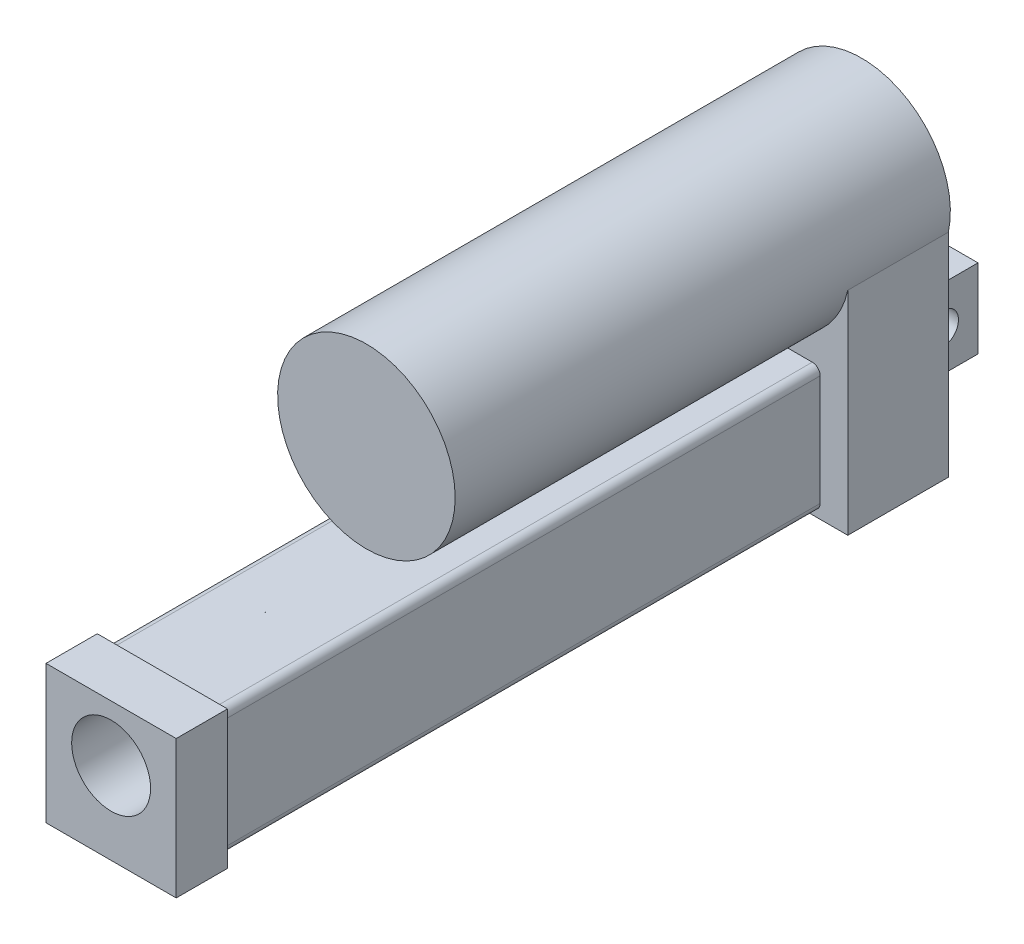
SolidWorks part; units mm, degrees
ref_plane "Front Plane" through (0, 0, 0) normal (0, 0, 1) x (1, 0, 0)
ref_plane "Top Plane" through (0, 0, 0) normal (0, 1, 0) x (1, 0, 0)
ref_plane "Right Plane" through (0, 0, 0) normal (1, 0, 0) x (0, 0, -1)
sketch "Sketch1" plane through (0, 0, 0) normal (0, 0, 1) x (1, 0, 0)
  line L0 (-22, -4.717) -> (-22, -58.5)
  line L3 (-22, -58.5) -> (22, -58.5)
  line L4 (22, -58.5) -> (22, -4.717)
  line L5 (0, 0) -> (0, -58.5) construction
  line L6 (0, 0) -> (0, 22.5) construction
  arc A2 (22, -4.717) -> (-22, -4.717) centre (0, 0) ccw
  dimension "D1" = 22.5
  dimension "D2" = 81
  dimension "D3" = 44
extrude "Boss-Extrude1" add sketch "Sketch1" along normal blind 25.5
sketch "Sketch2" plane through (0, 0, 25.5) normal (0, 0, 1) x (1, 0, 0)
  circle A0 centre (0, 0) radius 22.5
  dimension "D1" = 45
extrude "Boss-Extrude2" add sketch "Sketch2" along normal blind 100
sketch "Sketch3" plane through (0, 0, 25.5) normal (0, 0, 1) x (1, 0, 0)
  line L0 (0, -41) -> (0, -58.5) construction
  line L1 (-15, -57) -> (15, -57)
  line L2 (-15, -57) -> (-15, -25)
  line L3 (-15, -25) -> (15, -25)
  line L4 (15, -57) -> (15, -25)
  line L5 (-15, -57) -> (15, -25) construction
  line L6 (-15, -25) -> (15, -57) construction
  line L7 (-22, -58.5) -> (22, -58.5) construction
  point P0 (0, -41)
  dimension "D1" = 32
  dimension "D2" = 30
  dimension "D3" = 25
extrude "Boss-Extrude3" add sketch "Sketch3" along normal blind 164.7
sketch "Sketch4" plane through (0, 0, 0) normal (0, 0, -1) x (-1, 0, 0)
  line L0 (0, 0) -> (0, -37.7) construction
  line L2 (-9.5, -47.7) -> (9.5, -47.7)
  line L3 (-9.5, -47.7) -> (-9.5, -27.7)
  line L4 (-9.5, -27.7) -> (9.5, -27.7)
  line L5 (9.5, -47.7) -> (9.5, -27.7)
  line L6 (-9.5, -47.7) -> (9.5, -27.7) construction
  line L7 (-9.5, -27.7) -> (9.5, -47.7) construction
  line L8 (-15, -25) -> (15, -25) construction
  circle A0 centre (0, -37.7) radius 10 construction
  dimension "D4" = 20
  dimension "D1" = 19
  dimension "D2" = 20
  dimension "D3" = 2.7
extrude "Boss-Extrude4" add sketch "Sketch4" along normal blind 20
sketch "Sketch5" plane through (9.5, 0, 0) normal (1, 0, 0) x (0, 0, -1)
  line L0 (20, -37.7) -> (11, -37.7) construction
  line L1 (20, -27.7) -> (20, -47.7) construction
  line L2 (11, -37.7) -> (0, -37.7) construction
  line L3 (0, -58.5) -> (0, -4.717) construction
  circle A0 centre (11, -37.7) radius 4.05
  dimension "D2" = 8.1
  dimension "D1" = 11
extrude "Cut-Extrude1" cut sketch "Sketch5" against normal through all
sketch "Sketch6" plane through (0, 0, 190.2) normal (0, 0, 1) x (1, 0, 0)
  line L0 (0, -37.7) -> (9.5, -37.7) construction
  line L1 (9.5, -27.7) -> (9.5, -47.7) construction
  line L2 (0, 0) -> (0, -37.7) construction
  circle A0 centre (0, -37.7) radius 10
  dimension "D1" = 20
extrude "Boss-Extrude5" add sketch "Sketch6" along normal blind 25
sketch "Sketch7" plane through (0, 0, 190.2) normal (0, 0, 1) x (1, 0, 0)
  line L8 (16.5, -58.5) -> (16.5, -23.5)
  line L9 (16.5, -23.5) -> (-16.5, -23.5)
  line L10 (-16.5, -23.5) -> (-16.5, -58.5)
  line L11 (-16.5, -58.5) -> (16.5, -58.5)
  line L12 (16.5, -58.5) -> (16.5, -23.5)
  line L13 (16.5, -23.5) -> (-16.5, -23.5)
  line L14 (-16.5, -23.5) -> (-16.5, -58.5)
  line L15 (-16.5, -58.5) -> (16.5, -58.5)
  dimension "D1" = 1.5
extrude "Boss-Extrude6" add sketch "Sketch7" against normal blind 13
sketch "Sketch8" plane through (0, 0, 0) normal (1, 0, 0) x (0, 0, -1)
  line L0 (-215.2, -37.7) -> (-205.2, -37.7) construction
  line L1 (-215.2, -27.7) -> (-215.2, -47.7) construction
  line L2 (-205.2, -37.7) -> (-190.2, -37.7) construction
  line L3 (-190.2, -58.5) -> (-190.2, -23.5) construction
  circle A0 centre (-205.2, -37.7) radius 4.05
  circle A1 centre (11, -37.7) radius 4.05 construction
  dimension "D2" = 216.2
  dimension "D1" = 15
extrude "Cut-Extrude2" cut sketch "Sketch8" against normal through all both and the other way through all
fillet "Fillet1" radius 2 4 edges at (-15, -57, 101.35) (15, -57, 101.35) (-15, -25, 101.35) (15, -25, 101.35)
sketch "Sketch9" plane through (0, 0, 215.2) normal (0, 0, 1) x (1, 0, 0)
  circle A1 centre (0, -37.7) radius 10
  circle A2 centre (0, -37.7) radius 10
  dimension "D1" = 0
extrude "Cut-Extrude3" cut sketch "Sketch9" against normal blind 100
